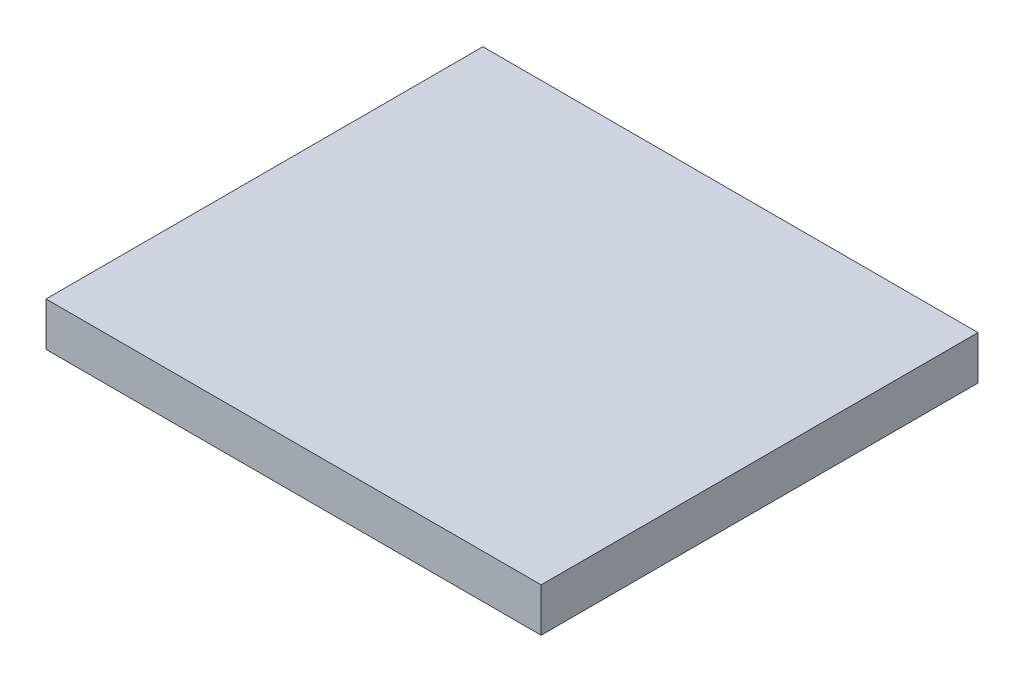
SolidWorks part; units mm, degrees
ref_plane "Plano frontal" through (0, 0, 0) normal (0, 0, 1) x (1, 0, 0)
ref_plane "Plano superior" through (0, 0, 0) normal (0, 1, 0) x (1, 0, 0)
ref_plane "Plano direito" through (0, 0, 0) normal (1, 0, 0) x (0, 0, -1)
sketch "Esboço1" plane through (0, 0, 0) normal (0, 0, 1) x (1, 0, 0)
  line L1 (0, 0) -> (-34, 0)
  line L2 (0, 0) -> (0, 3)
  line L3 (0, 3) -> (-34, 3)
  line L4 (-34, 0) -> (-34, 3)
  dimension "D1" = 34
  dimension "D2" = 3
extrude "Ressalto-extrusão1" add sketch "Esboço1" along normal blind 30
